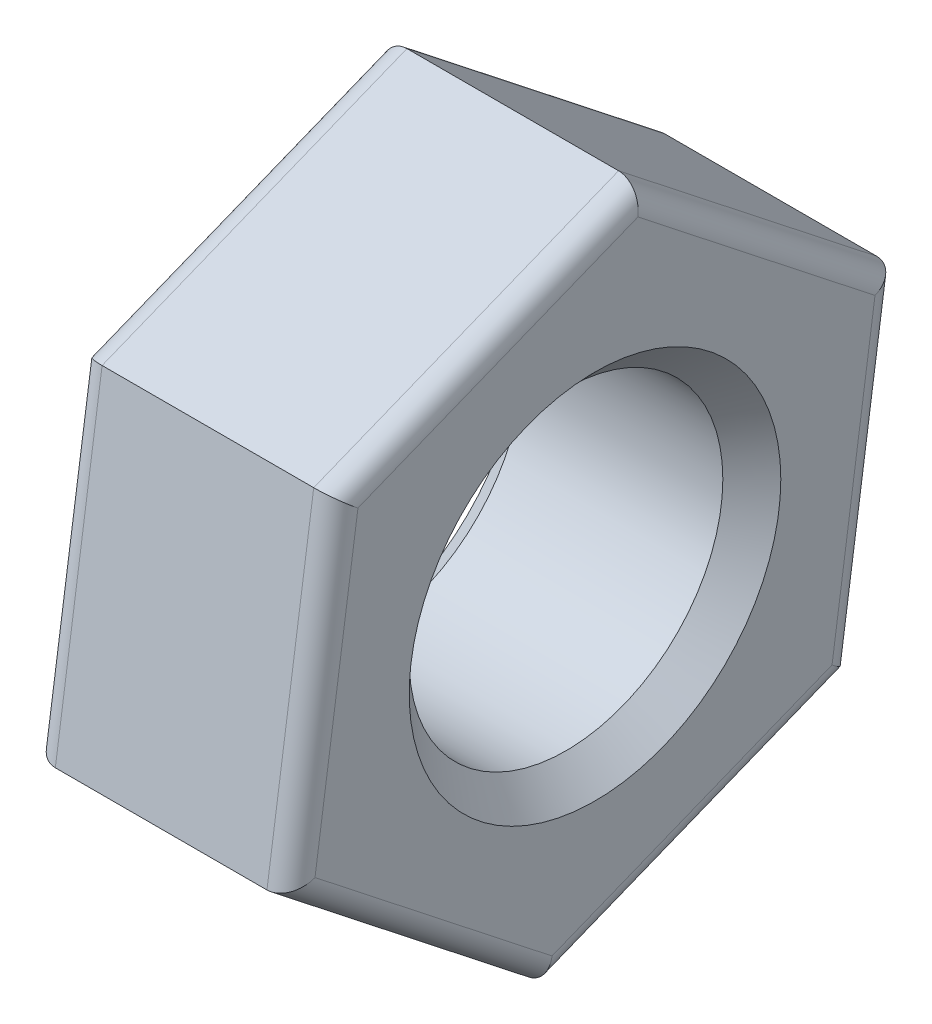
SolidWorks part; units mm, degrees
ref_plane "Front Plane" through (0, 0, 0) normal (0, 0, 1) x (1, 0, 0)
ref_plane "Top Plane" through (0, 0, 0) normal (0, 1, 0) x (1, 0, 0)
ref_plane "Right Plane" through (0, 0, 0) normal (1, 0, 0) x (0, 0, -1)
sketch "Sketch1" plane through (0, 0, 0) normal (1, 0, 0) x (0, 0, -1)
  line L1 (0.8066, 5.6061) -> (-4.4517, 3.5016)
  line L2 (-4.4517, 3.5016) -> (-5.2583, -2.1045)
  line L3 (-5.2583, -2.1045) -> (-0.8066, -5.6061)
  line L4 (-0.8066, -5.6061) -> (4.4517, -3.5016)
  line L5 (4.4517, -3.5016) -> (5.2583, 2.1045)
  line L6 (5.2583, 2.1045) -> (0.8066, 5.6061)
  circle A0 centre (0, 0) radius 4.905 construction
  circle A1 centre (0, 0) radius 2.705
  dimension "D2" = 5.41
  dimension "D1" = 9.81
extrude "Boss-Extrude1" add sketch "Sketch1" along normal blind 4.45
chamfer "Chamfer1" distance 0.5 angle 45 2 edges at (0, 0, -2.705) (4.45, 0, -2.705)
fillet "Fillet1" radius 0.4 12 edges at (0, -4.5538, -1.8225) (0, -0.6986, -4.855) (0, 3.8553, -3.0325) (0, 4.5538, 1.8225) (0, 0.6986, 4.855) (0, -3.8553, 3.0325) (4.45, -0.6986, -4.855) (4.45, 3.8553, -3.0325) (4.45, 4.5538, 1.8225) (4.45, 0.6986, 4.855) (4.45, -3.8553, 3.0325) (4.45, -4.5538, -1.8225)
